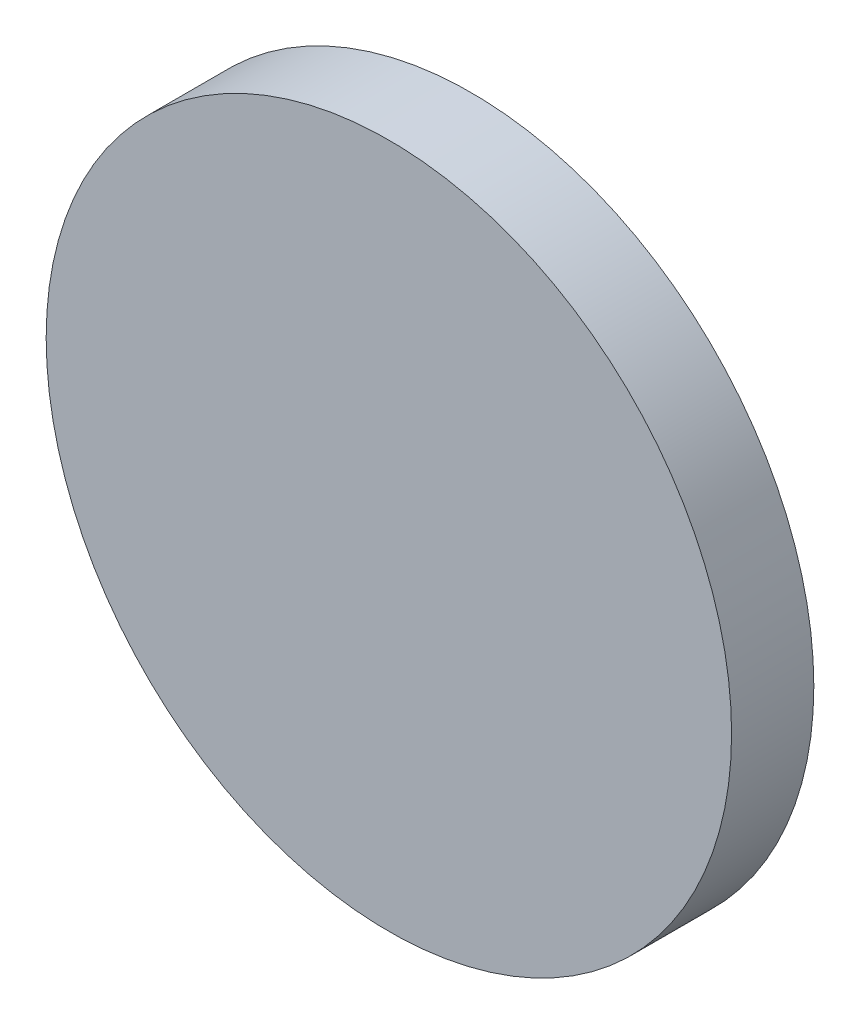
SolidWorks part; units mm, degrees
ref_plane "Front Plane" through (0, 0, 0) normal (0, 0, 1) x (1, 0, 0)
ref_plane "Top Plane" through (0, 0, 0) normal (0, 1, 0) x (1, 0, 0)
ref_plane "Right Plane" through (0, 0, 0) normal (1, 0, 0) x (0, 0, -1)
sketch "Sketch1" plane through (0, 0, 0) normal (0, 0, 1) x (1, 0, 0)
  circle A0 centre (0, 0) radius 12.5
  dimension "D1" = 25
extrude "Boss-Extrude1" add sketch "Sketch1" along normal blind 3
